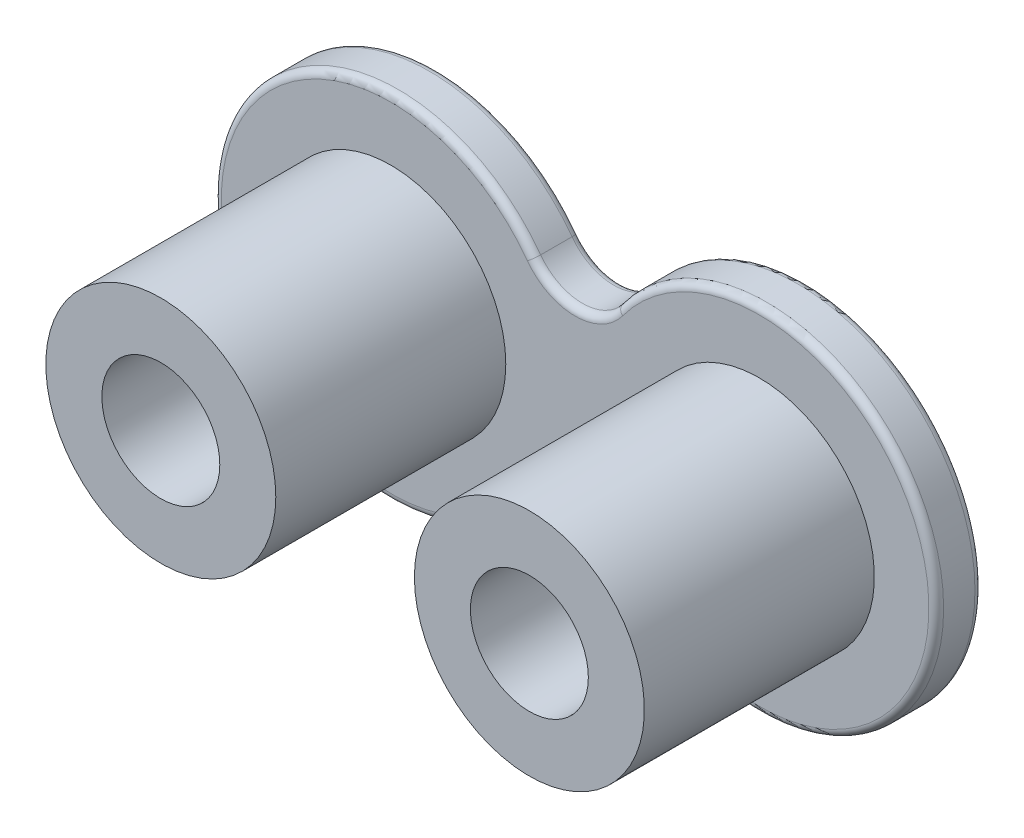
SolidWorks part; units mm, degrees
ref_plane "Front Plane" through (0, 0, 0) normal (0, 0, 1) x (1, 0, 0)
ref_plane "Top Plane" through (0, 0, 0) normal (0, 1, 0) x (1, 0, 0)
ref_plane "Right Plane" through (0, 0, 0) normal (1, 0, 0) x (0, 0, -1)
sketch "Sketch1" plane through (0, 0, 0) normal (0, 0, 1) x (1, 0, 0)
  line L0 (0, -0.3172) -> (0, 0.6403) construction
  line L1 (1.1978, 0) -> (-0.6265, 0) construction
  circle A0 centre (-6.35, 0) radius 2.032
  circle A3 centre (6.35, 0) radius 2.032
  arc A6 (-1.4387, 3.6112) -> (-1.4387, -3.6112) centre (-6.35, 0) ccw
  arc A7 (1.4387, -3.6112) -> (1.4387, 3.6112) centre (6.35, 0) ccw
  arc A8 (-1.4387, 3.6112) -> (1.4387, 3.6112) centre (0, 4.6691) ccw
  arc A9 (-1.4387, -3.6112) -> (1.4387, -3.6112) centre (0, -4.6691) cw
  point P12 (0, 0)
  dimension "D2" = 4.064
  dimension "D3" = 6.35
extrude "Boss-Extrude1" add sketch "Sketch1" along normal blind 1.5875
fillet "Fillet1" radius 0.254 12 edges at (4.318, 0, 0) (-4.318, 0, 0) (-12.446, 0, 0) (0, -2.8833, 0) (12.446, 0, 0) (0, 2.8833, 0) (4.318, 0, 1.5875) (12.446, 0, 1.5875) (0, -2.8833, 1.5875) (-12.446, 0, 1.5875) (0, 2.8833, 1.5875) (-4.318, 0, 1.5875)
sketch "Sketch5" plane through (0, 0, 1.5875) normal (0, 0, 1) x (1, 0, 0)
  line L0 (0, -5.3554) -> (0, 5.8427) construction
  circle A0 centre (-6.35, 0) radius 3.9624
  circle A1 centre (-6.35, 0) radius 2.032 construction
  circle A2 centre (-6.35, 0) radius 2.032
  circle A3 centre (6.35, 0) radius 3.9624
  circle A4 centre (6.35, 0) radius 2.032 construction
  circle A5 centre (6.35, 0) radius 2.032
  dimension "D1" = 7.9248
extrude "Boss-Extrude3" add sketch "Sketch5" along normal blind 7.9248
ref_plane "Plane1" through (0, 0, 5.5499) normal (0, 0, 1) x (1, 0, 0)
